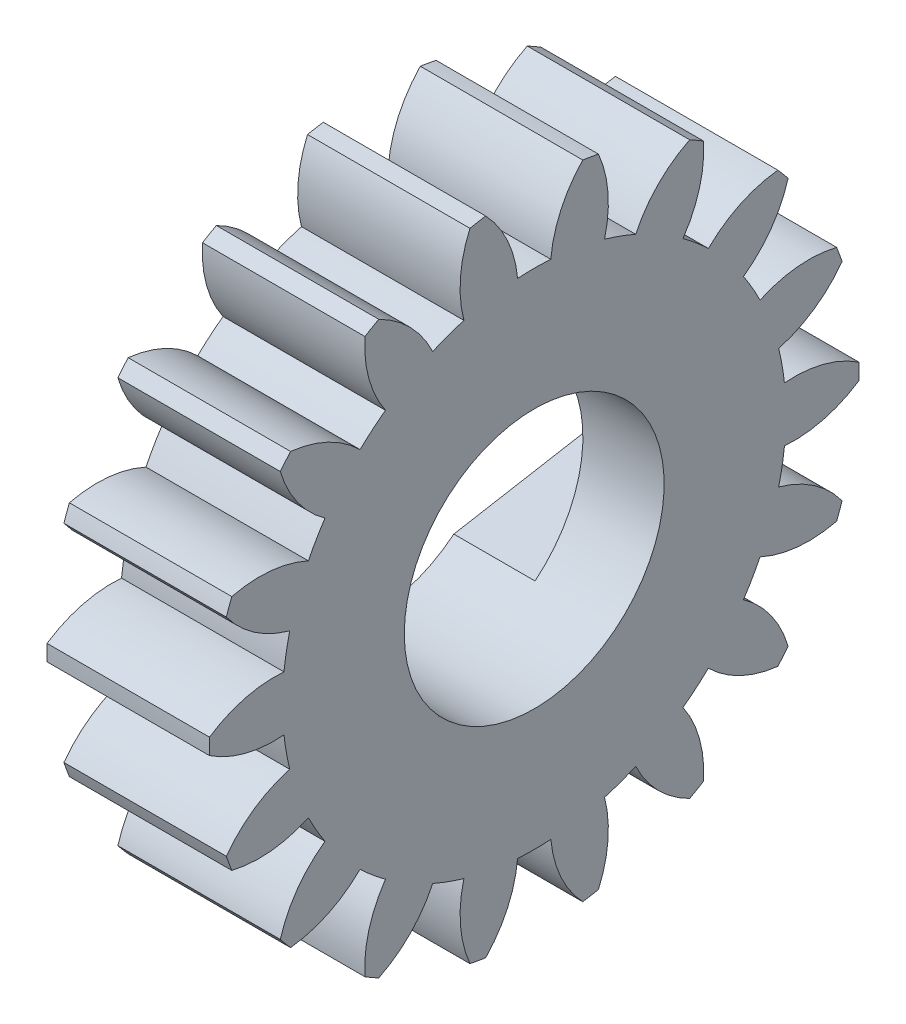
SolidWorks part; units mm, degrees
ref_plane "Plane1" through (0, 0, 0) normal (0, 0, 1) x (1, 0, 0)
ref_plane "Plane2" through (0, 0, 0) normal (0, 1, 0) x (1, 0, 0)
ref_plane "Plane3" through (0, 0, 0) normal (1, 0, 0) x (0, 0, -1)
other "Configuration Table"
sketch "HoldingSke" plane through (0, 0, 0) normal (0, 1, 0) x (1, 0, 0)
  line L0 (0, 0) -> (0.9511, -0.309)
  line L1 (-15, 0) -> (100, 0) construction
  line L2 (0, 0) -> (-2.1039, 2.3779)
  line L3 (0, 0) -> (-11.863, 4.5341)
  line L4 (0, 0) -> (8.2133, 2.6687)
  line L5 (0, 0) -> (-46.8476, -17.4728)
  line L6 (0, 0) -> (-4.1448, -2.7965)
  line L7 (-2.1039, 2.3779) -> (8.6586, 51.2059)
  line L8 (-76.2, 54.61) -> (-74.8, 54.61)
  line L9 (-71.009, 38.7566) -> (-53.1078, 45.2721)
  line L10 (-76.2, 71.12) -> (104.1128, 71.12)
  line L11 (0, 0) -> (-5, 0)
  line L12 (-76.2, 101.6) -> (-76.162, 101.6)
  line L13 (24.9733, 27.94) -> (52.9518, 28.4284)
  line L14 (24.9733, 27.94) -> (24.9743, 27.94)
  line L15 (24.9733, 27.94) -> (100.4006, 29.5858)
  line L16 (-63.627, -1) -> (-12.827, -1)
  circle A0 centre (0, 0) radius 4
  circle A1 centre (0, 0) radius 7.749
  circle A2 centre (0, 0) radius 37.5
  circle A3 centre (0, 0) radius 4
  dimension "MHD" = 15.498
  dimension "Hub_dia" = 75
  dimension "Bore" = 8
  dimension "MBD" = 8
  dimension "Num_teeth" = 18
  dimension "Pitch" = 1
  dimension "Overall_len" = 50
  dimension "Show_teeth" = 18
  dimension "Thickness" = 5
  dimension "OAL" = 50.0001
  dimension "T_dim" = 1.4
  dimension "Ap" = 20
  dimension "H" = 19.05
  dimension "Pitch_radius" = 180.3128
  dimension "Width" = 5
  dimension "Backlash" = 0.038
  dimension "Addendum_fac" = 1
  dimension "Dedendum_fac" = 1.25
  dimension "Clearance_fac" = 0.25
  dimension "Dedendum_add" = 0.001
  dimension "Module" = 1
sketch "BasProSke" plane through (0, 0, 0) normal (0, 1, 0) x (1, 0, 0)
  line L0 (-10, 0) -> (60, 0) construction
  line L1 (0, 0) -> (0, 10)
  line L2 (0, 0) -> (5, 0)
  line L3 (5, 0) -> (5, 10)
  line L4 (5, 10) -> (0, 10)
  dimension "Thickness" = 5
  dimension "Diameter" = 20
revolve "Base-Revolve" add sketch "BasProSke" angle 360 about L0
sketch "TooCutSke" plane through (0, 0, 0) normal (1, 0, 0) x (0, 0, -1)
  line L1 (0, 0) -> (0, 107) construction
  line L2 (0, 0) -> (-0.8509, 8.9597) construction
  line L3 (0, 0) -> (-3.1157, 17.6701) construction
  line L4 (-0.8509, 8.9597) -> (-1.5579, 8.835) construction
  arc A0 (0.5106, 7.7322) -> (-0.5106, 7.7322) centre (0, 0) ccw
  arc A1 (1.5152, 9.9102) -> (-1.5152, 9.9102) centre (0, 0) ccw
  circle A2 centre (0, 0) radius 9 construction
  circle A3 centre (0, 0) radius 8.4572 construction
  arc A4 (-0.5106, 7.7322) -> (-1.5152, 9.9102) centre (-4.0952, 7.3996) ccw
  arc A5 (1.5152, 9.9102) -> (0.5106, 7.7322) centre (4.0952, 7.3996) ccw
  dimension "Root_dia" = 15.498
  dimension "Overcut_dia" = 20.0508
  dimension "Pitch_dia" = 18
  dimension "Base_dia" = 16.9145
  dimension "Flank_rad" = 3.6
  dimension "Half_ang" = 10
  dimension "Half_CT" = 0.7179
extrude "ToothCut" cut sketch "TooCutSke" along normal through all
fillet "Breaks" [suppressed] radius 0.02
fillet "RootFillets" [suppressed] radius 0.251
pattern_circular "TeethCuts" count 18 every 20 about axis through (-10, 0, 0) along (1, 0, 0) of "ToothCut", "RootFillets", "Breaks"
sketch "HubNeaOneSke" plane through (0, 0, 0) normal (-1, 0, 0) x (0, 0, 1)
  circle A0 centre (0, 0) radius 7.749
  dimension "Diameter" = 15.498
extrude "HubNearOne" [suppressed] add sketch "HubNeaOneSke" along normal blind 45.0001
sketch "HubNeaBotSke" plane through (0, 0, 0) normal (-1, 0, 0) x (0, 0, 1)
  circle A0 centre (0, 0) radius 7.749
  dimension "Diameter" = 15.498
extrude "HubNearBoth" [suppressed] add sketch "HubNeaBotSke" along normal blind 22.5
ref_plane "FarPln" through (5, 0, 0) normal (1, 0, 0) x (0, 0, -1)
sketch "HubFarSke" plane through (5, 0, 0) normal (1, 0, 0) x (0, 0, -1)
  circle A0 centre (0, 0) radius 7.749
  dimension "Diameter" = 15.498
extrude "HubFar" [suppressed] add sketch "HubFarSke" along normal blind 22.5
sketch "BorSke" plane through (0, 0, 0) normal (1, 0, 0) x (0, 0, -1)
  circle A0 centre (0, 0) radius 4
  dimension "Diameter" = 8
extrude "Bore" cut sketch "BorSke" along normal mid plane 100.0001
sketch "KeySke" plane through (0, 0, 0) normal (1, 0, 0) x (0, 0, -1)
  line L0 (-1.5, 0) -> (-1.5, 5.4)
  line L1 (-1.5, 5.4) -> (1.5, 5.4)
  line L2 (1.5, 5.4) -> (1.5, 0)
  line L3 (0, 0) -> (0, 34) construction
  line L4 (-1.5, 0) -> (1.5, 0)
  dimension "Offset" = 5.4
  dimension "Width" = 3
extrude "Keyway" [suppressed] cut sketch "KeySke" along normal mid plane 100.0001
pattern_circular "Keyway2" [suppressed] count 2 every 90 about axis through (-10, 0, 0) along (1, 0, 0)
sketch "草图2" plane through (0, 0, 0) normal (-1, 0, 0) x (0, 0, 1)
  line L0 (0.3912, 3.4781) -> (-0.822, -3.4021)
  line L2 (-0.822, -3.4021) -> (-15.3617, -0.8384)
  line L3 (-15.3617, -0.8384) -> (-14.1486, 6.0418)
  line L4 (-14.1486, 6.0418) -> (0.3912, 3.4781)
  dimension "D1" = 6.9863
  dimension "D2" = 14.764
  dimension "D3" = 6.8802
extrude "切除-拉伸1" cut sketch "草图2" against normal blind 2.5
equation "' \"Module@HoldingSke\" = 6.35"
equation "' \"Num_teeth@HoldingSke\" = 12"
equation "' \"Ap@HoldingSke\" =  20"
equation "' \"Ap@HoldingSke\" = 20"
equation "' \"Width@HoldingSke\" = 0.5 * 25.4"
equation "' \"Hub_dia@HoldingSke\"= 1 * 25.4"
equation "' \"Hub_dia@HoldingSke\" = 1 * 25.4"
equation "' \"Overall_len@HoldingSke\" = 1.0 * 25.4"
equation "' \"Bore@HoldingSke\" = 0.75 * 25.4"
equation "' \"T_dim@HoldingSke\" = 0.1 * 25.4"
equation "' \"Width@KeySke\" = 0.25 * 25.4"
equation "' \"Show_teeth@HoldingSke\" = 13"
equation "' \"Backlash@HoldingSke\" = 0.009 * 25.4"
equation "' \"Addendum_fac@HoldingSke\" = 1.0"
equation "' \"Dedendum_fac@HoldingSke\" = 1.25"
equation "' \"Dedendum_add@HoldingSke\" = 0.00005 * 25.4"
equation "' \"Clearance_fac@HoldingSke\" = 0.25"
equation "\"Pitch@HoldingSke\" = 1 / \"Module@HoldingSke\""
equation "\"Overcut_dia@TooCutSke\" = (\"Num_teeth@HoldingSke\" + 2 * \"Addendum_fac@HoldingSke\") / \"Pitch@HoldingSke\" + 0.002 * 25.4"
equation "\"Pitch_dia@TooCutSke\" = \"Num_teeth@HoldingSke\" / \"Pitch@HoldingSke\""
equation "\"Base_dia@TooCutSke\" = \"Num_teeth@HoldingSke\" / \"Pitch@HoldingSke\" * cos((\"Ap@HoldingSke\"  * 3.14159265 / 180))"
equation "\"Root_dia@TooCutSke\" = (\"Num_teeth@HoldingSke\" + 2) / \"Pitch@HoldingSke\" - 2 * (\"Addendum_fac@HoldingSke\" + \"Dedendum_fac@HoldingSke\") / \"Pitch@HoldingSke\" - \"Dedendum_add@HoldingSke\" * 2"
equation "\"Half_ang@TooCutSke\" = 180 / \"Num_teeth@HoldingSke\""
equation "\"Half_CT@TooCutSke\" = \"Num_teeth@HoldingSke\" / \"Pitch@HoldingSke\" * sin((3.14159265 / 2 / \"Num_teeth@HoldingSke\")) / 2 - 7 * \"Backlash@HoldingSke\" / 4"
equation "\"Flank_rad@TooCutSke\" = \"Num_teeth@HoldingSke\" / \"Pitch@HoldingSke\" / 5"
equation "\"Radius@RootFillets\" = \"Clearance_fac@HoldingSke\" / \"Pitch@HoldingSke\" + \"Dedendum_add@HoldingSke\""
equation "\"Break_rad@Breaks\" = 0.02 / \"Pitch@HoldingSke\""
equation "\"Thickness@HoldingSke\" = \"Width@HoldingSke\""
equation "\"OAL@HoldingSke\" = \"Thickness@HoldingSke\""
equation "\"MHD@HoldingSke\" = (\"Num_teeth@HoldingSke\" + 2) / \"Pitch@HoldingSke\" - 2 * (\"Addendum_fac@HoldingSke\" + \"Dedendum_fac@HoldingSke\")  / \"Pitch@HoldingSke\" - \"Dedendum_add@HoldingSke\" * 2"
equation "\"MBD@HoldingSke\" = (\"Num_teeth@HoldingSke\" + 2) / \"Pitch@HoldingSke\" - 2 * (\"Addendum_fac@HoldingSke\" + \"Dedendum_fac@HoldingSke\")  / \"Pitch@HoldingSke\" - \"Dedendum_add@HoldingSke\" * 2 - 0.002 * 25.4"
equation "\"MHD@HoldingSke\" = ((sgn( \"MHD@HoldingSke\" - \"Hub_dia@HoldingSke\" )-1)*( \"MHD@HoldingSke\" - \"Hub_dia@HoldingSke\" ))/-2+ \"Hub_dia@HoldingSke\""
equation "\"MBD@HoldingSke\" = ((sgn( \"MBD@HoldingSke\" - \"Bore@HoldingSke\" )-1)*( \"MBD@HoldingSke\" - \"Bore@HoldingSke\" ))/-2+ \"Bore@HoldingSke\""
equation "\"OAL@HoldingSke\" = ((sgn( \"OAL@HoldingSke\" - \"Overall_len@HoldingSke\" )+1)*( \"OAL@HoldingSke\" - \"Overall_len@HoldingSke\" ))/2 + \"Overall_len@HoldingSke\" + 0.000002 * 25.4"
equation "\"Num_teeth@TeethCuts\" = int( \"Show_teeth@HoldingSke\" ) + 1"
equation "\"Num_teeth@TeethCuts\" = ((sgn( \"Num_teeth@TeethCuts\" - \"Num_teeth@HoldingSke\" )-1)*( \"Num_teeth@TeethCuts\" - \"Num_teeth@HoldingSke\" ))/-2+ \"Num_teeth@HoldingSke\""
equation "\"Num_teeth@TeethCuts\" = ((sgn( \"Num_teeth@TeethCuts\" - 2.0)+1)*( \"Num_teeth@TeethCuts\" - 2.0))/2 +2.0"
equation "\"Angle@TeethCuts\" = 360.0 / \"Num_teeth@HoldingSke\""
equation "\"Diameter@BasProSke\" = (\"Num_teeth@HoldingSke\" + 2 * \"Addendum_fac@HoldingSke\") / \"Pitch@HoldingSke\""
equation "\"Thickness@BasProSke\"  = \"Thickness@HoldingSke\""
equation "' \"Fillet_rad@BasProSke\" =  \"Thickness@HoldingSke\" * 0.05"
equation "' \"Fillet_rad@BasProSke\" = \"Thickness@HoldingSke\" * 0.05"
equation "\"MHD@HoldingSke\" = ((sgn( \"MHD@HoldingSke\" - \"Root_dia@TooCutSke\" )-1)*( \"MHD@HoldingSke\" - \"Root_dia@TooCutSke\" ))/-2+ \"Root_dia@TooCutSke\""
equation "\"Diameter@HubNeaOneSke\" = \"MHD@HoldingSke\""
equation "\"Length@HubNearOne\" = \"OAL@HoldingSke\" - \"Thickness@BasProSke\""
equation "\"Diameter@HubNeaBotSke\" = \"MHD@HoldingSke\""
equation "\"Length@HubNearBoth\" = ( \"OAL@HoldingSke\" - \"Thickness@BasProSke\" ) / 2.0"
equation "\"Thickness@FarPln\" = \"Thickness@BasProSke\""
equation "\"Diameter@HubFarSke\" = \"MHD@HoldingSke\""
equation "\"Length@HubFar\" = ( \"OAL@HoldingSke\" - \"Thickness@BasProSke\" ) / 2.0"
equation "\"Diameter@BorSke\" = \"MBD@HoldingSke\""
equation "\"D1@Bore\" = \"OAL@HoldingSke\" * 2.0"
equation "\"D1@Keyway\" = \"OAL@HoldingSke\" * 2.0"
equation "\"Offset@KeySke\" = \"T_dim@HoldingSke\" + \"MBD@HoldingSke\" / 2.0"
